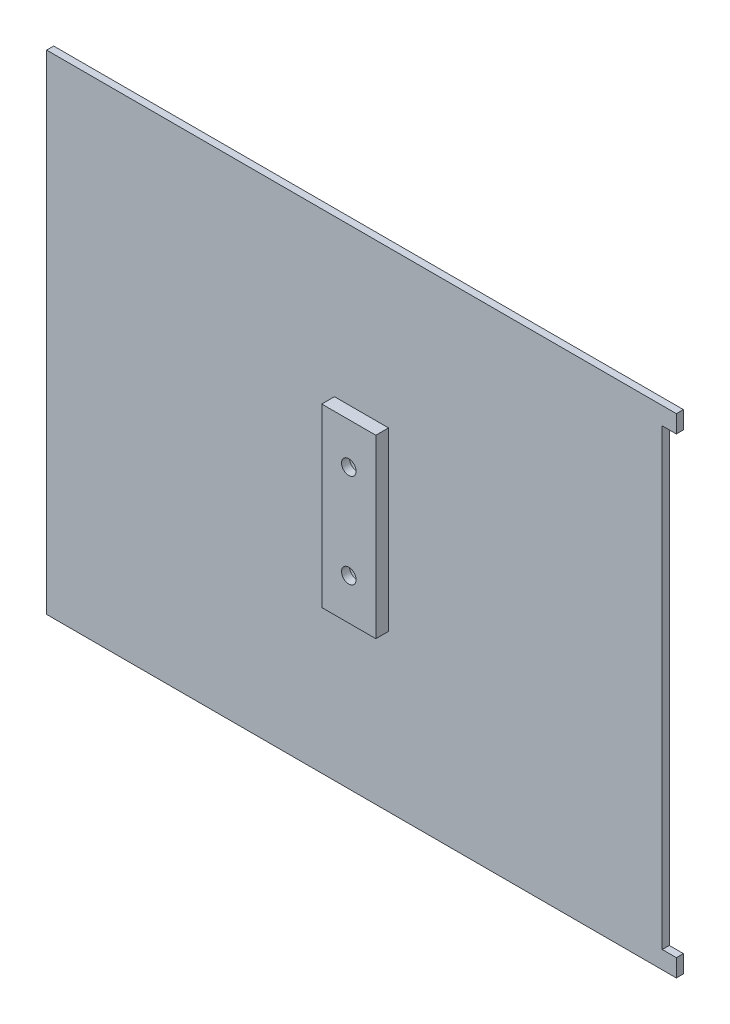
SolidWorks part; units mm, degrees
ref_plane "Спереди" through (0, 0, 0) normal (0, 0, 1) x (1, 0, 0)
ref_plane "Сверху" through (0, 0, 0) normal (0, 1, 0) x (1, 0, 0)
ref_plane "Справа" through (0, 0, 0) normal (1, 0, 0) x (0, 0, -1)
sketch "Эскиз1" plane through (0, 0, 0) normal (0, 0, 1) x (1, 0, 0)
  line L0 (67, 0) -> (0, 0) construction
  line L1 (67, -52) -> (-67, -52)
  line L2 (67, -52) -> (67, -48.25)
  line L3 (67, 52) -> (-67, 52)
  line L4 (-67, -52) -> (-67, 52)
  line L5 (67, -52) -> (-67, 52) construction
  line L6 (67, 52) -> (-67, -52) construction
  line L7 (67, 0) -> (67, 52)
  line L8 (67, -48.25) -> (64, -48.25)
  line L10 (67, 48.25) -> (64, 48.25)
  line L11 (64, -48.25) -> (64, 48.25)
  line L12 (67, 0) -> (64, 48.25) construction
  line L13 (67, 0) -> (64, -48.25) construction
  point P0 (0, 0)
  point P6 (67, 0)
  point P7 (67, 48.25)
  point P10 (67, -48.25)
  dimension "D1" = 104
  dimension "D2" = 134
  dimension "D3" = 48.25
extrude "Бобышка-Вытянуть2" add sketch "Эскиз1" along normal blind 1.5 contours L8 L11 L10 L7 L3 L4 L1 L2
sketch "Эскиз2" plane through (0, 0, 1.5) normal (0, 0, 1) x (1, 0, 0)
  line L1 (5.75, -18.75) -> (-5.75, -18.75)
  line L2 (5.75, -18.75) -> (5.75, 18.75)
  line L3 (5.75, 18.75) -> (-5.75, 18.75)
  line L4 (-5.75, -18.75) -> (-5.75, 18.75)
  line L5 (5.75, -18.75) -> (-5.75, 18.75) construction
  line L6 (5.75, 18.75) -> (-5.75, -18.75) construction
  point P0 (0, 0)
  dimension "D1" = 37.5
  dimension "D2" = 11.5
extrude "Бобышка-Вытянуть3" add sketch "Эскиз2" along normal blind 2.7
sketch "Эскиз3" plane through (0, 0, 0) normal (0, 0, -1) x (-1, 0, 0)
  circle A0 centre (0, -10) radius 3.1
  circle A1 centre (0, 10) radius 3.1
  point P0 (0, -10)
  point P1 (0, 10)
  dimension "D3" = 6.2
  dimension "D4" = 6.2
  dimension "D1" = 10
  dimension "D2" = 10
extrude "Вырез-Вытянуть1" cut sketch "Эскиз3" against normal blind 2.5
sketch "Эскиз4" plane through (0, 0, 2.5) normal (0, 0, -1) x (-1, 0, 0)
  circle A0 centre (0, -10) radius 1.55
  circle A1 centre (0, 10) radius 1.55
  point P0 (0, 10)
  point P1 (0, -10)
  dimension "D1" = 3.1
  dimension "D2" = 3.1
extrude "Вырез-Вытянуть2" cut sketch "Эскиз4" against normal blind 2.5
